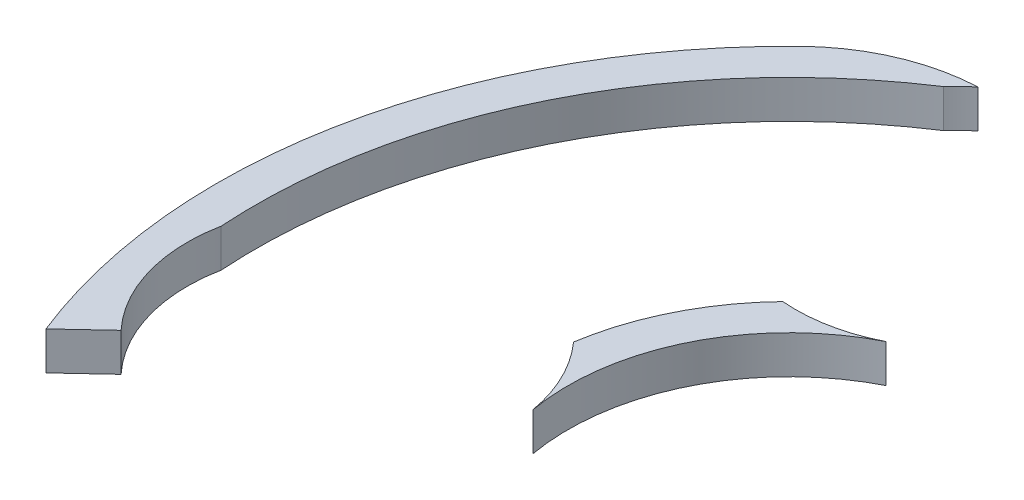
SolidWorks part; units mm, degrees
ref_plane "Plan de face" through (0, 0, 0) normal (0, 0, 1) x (1, 0, 0)
ref_plane "Plan de dessus" through (0, 0, 0) normal (0, 1, 0) x (1, 0, 0)
ref_plane "Plan de droite" through (0, 0, 0) normal (1, 0, 0) x (0, 0, -1)
sketch "Esquisse1" plane through (0, 0, 0) normal (0, 1, 0) x (1, 0, 0)
  line L0 (-85.9864, -39.221) -> (-80.901, -34.4645)
  line L3 (-9.4508, 5.6286) -> (-14.9085, -3.5351) construction
  line L5 (3.3105, -15.9387) -> (9.4508, -5.6286) construction
  line L12 (0, 0) -> (-80, 0) construction
  line L13 (-64.4502, -24.994) -> (-51.2217, 24.3754) construction
  line L14 (-65, 0) -> (-64.4502, -24.994) construction
  arc A0 (-44.8834, -16.4709) -> (3.3105, -15.9387) centre (-21.2415, 25) ccw construction
  arc A1 (-20.1052, -3.4627) -> (-14.9085, -3.5351) centre (-17.486, -2) ccw construction
  arc A2 (-20.1052, -3.4627) -> (-29.494, 14.405) centre (325.5264, 189.5538) cw construction
  arc A3 (-13.5326, 17.4331) -> (-23.8264, -39.4451) centre (-16.3245, -11.4322) ccw
  arc A4 (-40.7805, 12.1878) -> (-49.9076, -6.124) centre (-16.3245, -11.4322) ccw
  arc A5 (-13.0513, 22.4098) -> (-25.1198, -44.2749) centre (-16.3245, -11.4322) ccw construction
  arc A6 (-54.6669, 47.1327) -> (-86.1705, -16.0732) centre (-16.3245, -11.4322) ccw
  arc A36 (-51.2217, 24.3754) -> (-64.4502, -24.994) centre (-16.3245, -11.4322) ccw construction
  arc A37 (-68.6703, 42.2792) -> (-85.9864, -39.221) centre (-16.3245, -11.4322) ccw
  arc A41 (9.4508, -5.6286) -> (-9.4508, 5.6286) centre (0, 0) ccw construction
  arc A42 (-16.402, 38.5677) -> (-47.4539, -50.5598) centre (-16.3245, -11.4322) ccw construction
  arc A43 (-52.3505, 49.3499) -> (-29.494, 14.405) centre (-39.0306, 33.1147) ccw
  arc A44 (-52.3505, 49.3499) -> (-68.6703, 42.2792) centre (-51.2217, 24.3754) ccw
  arc A45 (-44.8834, -16.4709) -> (-80.901, -34.4645) centre (-65.564, -20.1196) ccw
  point P78 (-56.6847, 2.6915)
  point P85 (-65, 0)
  dimension "D4" = 25
  dimension "D5" = 12
  dimension "D6" = 21
  dimension "D7" = 5
  dimension "D8" = 25
  dimension "D9" = 5
  dimension "D10" = 3
  dimension "D11" = 17.6
  dimension "D18" = 80
  dimension "D20" = 75
  dimension "D26" = 11
  dimension "D13" = 50
  dimension "D14" = 21
  dimension "D12" = 2
  dimension "D22" = 25
  dimension "D23" = 75
  dimension "D24" = 28
  dimension "D25" = 15
  dimension "D30" = 15
  dimension "D32" = 5
extrude "Boss.-Extru.1" add sketch "Esquisse1" along normal blind 5 contours A45 A3 A43 A44 A37 L0 | A45 A3 A43 A4
